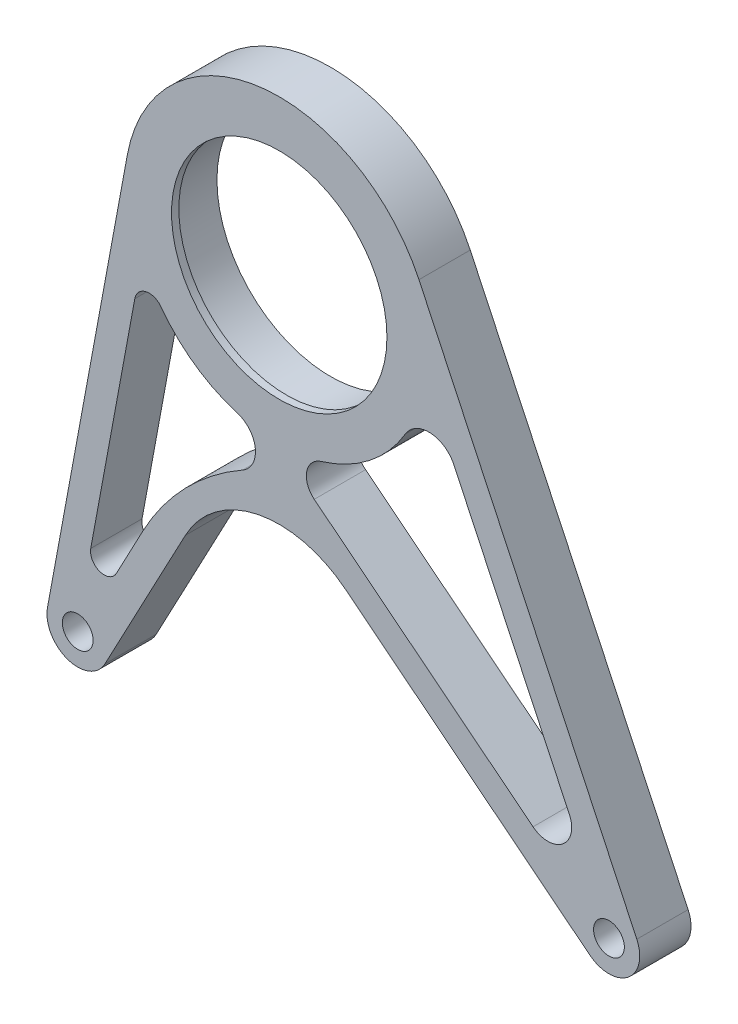
SolidWorks part; units mm, degrees
material "7075-T6 (SN)"
ref_plane "Front Plane" through (0, 0, 0) normal (0, 0, 1) x (1, 0, 0)
ref_plane "Top Plane" through (0, 0, 0) normal (0, 1, 0) x (1, 0, 0)
ref_plane "Right Plane" through (0, 0, 0) normal (1, 0, 0) x (0, 0, -1)
sketch "Sketch1" plane through (0, 0, 0) normal (0, 0, 1) x (1, 0, 0)
  line L0 (-41.4573, 7.6656) -> (-63.26, -110.2491)
  line L1 (-47.58, -115.7138) -> (-25.6167, -74.3244)
  line L2 (18.065, -65.2319) -> (84.7674, -118.3475)
  line L3 (97.5984, -108.1954) -> (38.1369, 17.9734)
  line L4 (0, -58.9179) -> (0, -176.4178) construction
  line L8 (90, -111.7764) -> (-55, -111.7764) construction
  line L10 (0, 0) -> (0, -31) construction
  circle A0 centre (0, 0) radius 31
  arc A1 (38.1369, 17.9734) -> (-41.4573, 7.6656) centre (0, 0) ccw
  arc A4 (-47.58, -115.7138) -> (-63.26, -110.2491) centre (-55, -111.7764) cw
  arc A6 (84.7674, -118.3475) -> (97.5984, -108.1954) centre (90, -111.7764) ccw
  arc A7 (18.065, -65.2319) -> (-25.6167, -74.3244) centre (0, -87.9179) ccw
  circle A8 centre (-55, -111.7764) radius 4.2
  circle A9 centre (90, -111.7764) radius 4.2
  point P10 (0, 0)
  point P24 (0, -65.6103)
  dimension "D1" = 62
  dimension "D2" = 84.32
  dimension "D3" = 8.4
  dimension "D4" = 8.4
  dimension "D6" = 29
  dimension "D7" = 8.4
  dimension "D8" = 55
  dimension "D9" = 90
extrude "Boss-Extrude1" add sketch "Sketch1" along normal mid plane 14 contours L0 A4 L1 A7 L2 A6 L3 A1
sketch "Sketch3" plane through (0, 0, 7) normal (0, 0, 1) x (1, 0, 0)
  circle A0 centre (-55, -111.7764) radius 4.2
  circle A1 centre (90, -111.7764) radius 4.2
  circle A2 centre (0, 0) radius 31
  dimension "D1" = 62
extrude "Cut-Extrude1" cut sketch "Sketch3" against normal through all
sketch "Sketch5" plane through (0, 0, 7) normal (0, 0, 1) x (1, 0, 0)
  circle A0 centre (0, 0) radius 31
  circle A1 centre (0, 0) radius 29.4
  dimension "D1" = 62
  dimension "D2" = 58.8
extrude "Boss-Extrude3" add sketch "Sketch5" against normal blind 2
sketch "Sketch7" plane through (0, 0, -7) normal (0, 0, -1) x (-1, 0, 0)
  line L3 (39.4166, -25.2974) -> (51.4441, -90.3454)
  line L4 (41.4573, 7.6656) -> (63.26, -110.2491) construction
  line L5 (-47.6599, -20.9985) -> (-79.2025, -87.9274)
  line L7 (-97.5984, -108.1954) -> (-38.1369, 17.9734) construction
  line L8 (44.4655, -92.7776) -> (37.2247, -79.1324)
  line L9 (-69.2737, -95.7832) -> (-9.5587, -48.2317)
  line L10 (-18.065, -65.2319) -> (-84.7674, -118.3475) construction
  line L11 (47.58, -115.7138) -> (25.6167, -74.3244) construction
  arc A12 (39.4166, -25.2974) -> (32.2537, -23.658) centre (35.481, -26.0251) ccw
  arc A20 (11.4732, -38.3193) -> (32.2537, -23.658) centre (0, 0) ccw
  arc A22 (-9.5587, -48.2317) -> (-11.4732, -38.3193) centre (-13.1069, -43.7759) ccw
  arc A23 (-34.4215, -20.3755) -> (-47.6599, -20.9985) centre (-40.8756, -24.1959) ccw
  arc A24 (-79.2025, -87.9274) -> (-69.2737, -95.7832) centre (-73.3227, -90.6984) ccw
  arc A25 (-34.4215, -20.3755) -> (-11.4732, -38.3193) centre (0, 0) ccw
  arc A27 (44.4655, -92.7776) -> (51.4441, -90.3454) centre (47.7679, -91.0251) ccw
  arc A29 (11.4732, -38.3193) -> (10.0183, -51.1087) centre (13.481, -45.0251) ccw
  arc A30 (37.2247, -79.1324) -> (10.0183, -51.1087) centre (-24.6088, -111.9443) ccw
  dimension "D2" = 40
  dimension "D3" = 8
  dimension "D4" = 8
  dimension "D5" = 40
  dimension "D9" = 6.5
  dimension "D10" = 7.5
  dimension "D12" = 22
  dimension "D13" = 19
  dimension "D7" = 8
  dimension "D11" = 7
  dimension "D6" = 70
  dimension "D8" = 8
  dimension "D14" = 65
extrude "Cut-Extrude3" cut sketch "Sketch7" against normal through all
